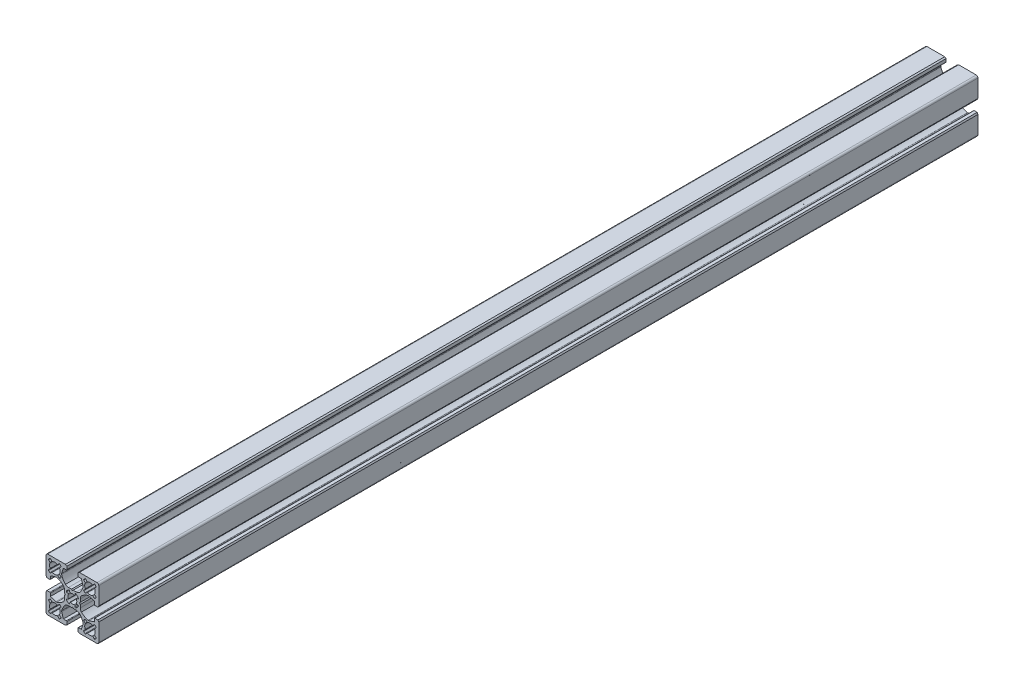
SolidWorks part; units mm, degrees
ref_plane "정면" through (0, 0, 0) normal (0, 0, 1) x (1, 0, 0)
ref_plane "윗면" through (0, 0, 0) normal (0, 1, 0) x (1, 0, 0)
ref_plane "우측면" through (0, 0, 0) normal (1, 0, 0) x (0, 0, -1)
sketch "Model" plane through (0, 0, 0) normal (0, 0, 1) x (1, 0, 0)
  line L0 (465.6218, 205.5838) -> (465.6218, 209.9838) construction
  line L1 (463.4218, 207.7838) -> (467.8218, 207.7838) construction
  line L2 (462.8793, 206.102) -> (462.1388, 205.3614)
  line L3 (463.1994, 204.3007) -> (463.94, 205.0413)
  line L4 (467.3037, 205.0413) -> (468.0443, 204.3007)
  line L5 (469.1049, 205.3614) -> (468.3643, 206.102)
  line L6 (468.3643, 209.4657) -> (469.1049, 210.2063)
  line L7 (468.0443, 211.2669) -> (467.3037, 210.5263)
  line L8 (463.94, 210.5263) -> (463.1994, 211.2669)
  line L9 (462.1388, 210.2063) -> (462.8793, 209.4657)
  line L10 (463.4211, 187.7832) -> (467.8211, 187.7829) construction
  line L11 (465.6212, 189.9831) -> (465.6209, 185.5831) construction
  line L12 (462.8787, 189.4651) -> (462.1382, 190.2057)
  line L13 (463.1989, 191.2663) -> (463.9394, 190.5257)
  line L14 (467.3031, 190.5254) -> (468.0438, 191.2659)
  line L15 (469.1043, 190.2052) -> (468.3637, 189.4647)
  line L16 (468.3634, 186.101) -> (469.1039, 185.3604)
  line L17 (468.0432, 184.2998) -> (467.3027, 185.0404)
  line L18 (463.939, 185.0407) -> (463.1984, 184.3002)
  line L19 (462.1378, 185.3609) -> (462.8784, 186.1014)
  line L20 (448.3673, 189.4651) -> (449.1078, 190.2057)
  line L21 (448.0471, 191.2663) -> (447.3066, 190.5257)
  line L22 (443.9429, 190.5254) -> (443.2023, 191.2659)
  line L23 (442.1417, 190.2052) -> (442.8823, 189.4647)
  line L24 (442.8826, 186.101) -> (442.1421, 185.3604)
  line L25 (443.2028, 184.2998) -> (443.9433, 185.0404)
  line L26 (447.307, 185.0407) -> (448.0476, 184.3002)
  line L27 (449.1082, 185.3609) -> (448.3676, 186.1014)
  line L28 (445.6248, 189.9831) -> (445.6251, 185.5831) construction
  line L29 (447.825, 187.7832) -> (443.425, 187.7829) construction
  line L30 (447.8242, 207.7838) -> (443.4242, 207.7838) construction
  line L31 (445.6242, 205.5838) -> (445.6242, 209.9838) construction
  line L32 (471.0819, 197.7838) -> (439.4, 197.7838) construction
  line L33 (455.6242, 181.8427) -> (455.6242, 213.7801) construction
  line L34 (457.2103, 201.0212) -> (457.0767, 200.2802)
  line L35 (454.1716, 200.2802) -> (454.0381, 201.0212)
  line L36 (452.3868, 199.37) -> (453.1278, 199.2364)
  line L37 (453.1278, 196.3313) -> (452.3868, 196.1977)
  line L38 (454.0381, 194.5465) -> (454.1716, 195.2874)
  line L39 (457.0767, 195.2874) -> (457.2103, 194.5465)
  line L40 (458.8615, 196.1977) -> (458.1206, 196.3313)
  line L41 (458.1206, 199.2364) -> (458.8615, 199.37)
  line L42 (448.3667, 206.102) -> (449.1073, 205.3614)
  line L43 (448.0466, 204.3007) -> (447.306, 205.0413)
  line L44 (443.9423, 205.0413) -> (443.2018, 204.3007)
  line L45 (442.1411, 205.3614) -> (442.8817, 206.102)
  line L46 (442.8817, 209.4657) -> (442.1411, 210.2063)
  line L47 (443.2018, 211.2669) -> (443.9423, 210.5263)
  line L48 (447.306, 210.5263) -> (448.0466, 211.2669)
  line L49 (449.1073, 210.2063) -> (448.3667, 209.4657)
  line L50 (459.5742, 182.7838) -> (458.7742, 183.2838)
  line L51 (458.7742, 183.2838) -> (458.7742, 184.9838)
  line L52 (459.0742, 185.2838) -> (460.7242, 185.2838)
  line L53 (460.7242, 185.2838) -> (461.7118, 188.3356)
  line L54 (457.842, 193.2838) -> (456.1242, 193.2838)
  line L55 (456.1242, 193.2838) -> (455.6242, 193.7838)
  line L56 (455.6242, 193.7838) -> (455.1242, 193.2838)
  line L57 (455.1242, 193.2838) -> (453.4063, 193.2838)
  line L58 (449.5366, 188.3356) -> (450.5242, 185.2838)
  line L59 (450.5242, 185.2838) -> (452.1742, 185.2838)
  line L60 (452.4742, 184.9838) -> (452.4742, 183.2838)
  line L61 (452.4742, 183.2838) -> (451.6742, 182.7838)
  line L62 (451.6742, 182.7838) -> (441.6242, 182.7838)
  line L63 (440.6242, 183.7838) -> (440.6242, 193.8338)
  line L64 (440.6242, 193.8338) -> (441.1242, 194.6338)
  line L65 (441.1242, 194.6338) -> (442.8242, 194.6338)
  line L66 (443.1242, 194.3338) -> (443.1242, 192.6838)
  line L67 (443.1242, 192.6838) -> (446.1759, 191.6962)
  line L68 (451.1242, 195.566) -> (451.1242, 197.2838)
  line L69 (451.1242, 197.2838) -> (451.6242, 197.7838)
  line L70 (451.6242, 197.7838) -> (451.1242, 198.2838)
  line L71 (451.1242, 198.2838) -> (451.1242, 200.0017)
  line L72 (446.1759, 203.8714) -> (443.1242, 202.8838)
  line L73 (443.1242, 202.8838) -> (443.1242, 201.2338)
  line L74 (442.8242, 200.9338) -> (441.1242, 200.9338)
  line L75 (441.1242, 200.9338) -> (440.6242, 201.7338)
  line L76 (440.6242, 201.7338) -> (440.6242, 211.7838)
  line L77 (441.6242, 212.7838) -> (451.6742, 212.7838)
  line L78 (451.6742, 212.7838) -> (452.4742, 212.2838)
  line L79 (452.4742, 212.2838) -> (452.4742, 210.5838)
  line L80 (452.1742, 210.2838) -> (450.5242, 210.2838)
  line L81 (450.5242, 210.2838) -> (449.5366, 207.2321)
  line L82 (453.4063, 202.2838) -> (455.1242, 202.2838)
  line L83 (455.1242, 202.2838) -> (455.6242, 201.7838)
  line L84 (455.6242, 201.7838) -> (456.1242, 202.2838)
  line L85 (456.1242, 202.2838) -> (457.842, 202.2838)
  line L86 (461.7118, 207.2321) -> (460.7242, 210.2838)
  line L87 (460.7242, 210.2838) -> (459.0742, 210.2838)
  line L88 (458.7742, 210.5838) -> (458.7742, 212.2838)
  line L89 (458.7742, 212.2838) -> (459.5742, 212.7838)
  line L90 (459.5742, 212.7838) -> (469.6242, 212.7838)
  line L91 (470.6242, 211.7838) -> (470.6242, 201.7338)
  line L92 (470.6242, 201.7338) -> (470.1242, 200.9338)
  line L93 (470.1242, 200.9338) -> (468.4242, 200.9338)
  line L94 (468.1242, 201.2338) -> (468.1242, 202.8838)
  line L95 (468.1242, 202.8838) -> (465.0724, 203.8714)
  line L96 (460.1242, 200.0017) -> (460.1242, 198.2838)
  line L97 (460.1242, 198.2838) -> (459.6242, 197.7838)
  line L98 (459.6242, 197.7838) -> (460.1242, 197.2838)
  line L99 (460.1242, 197.2838) -> (460.1242, 195.566)
  line L100 (465.0724, 191.6962) -> (468.1242, 192.6838)
  line L101 (468.1242, 192.6838) -> (468.1242, 194.3338)
  line L102 (468.4242, 194.6338) -> (470.1242, 194.6338)
  line L103 (470.1242, 194.6338) -> (470.6242, 193.8338)
  line L104 (470.6242, 193.8338) -> (470.6242, 183.7838)
  line L105 (469.6242, 182.7838) -> (459.5742, 182.7838)
  arc A0 (462.8793, 206.102) -> (462.9358, 206.4477) centre (462.6672, 206.3141) ccw
  arc A1 (462.1388, 205.3614) -> (462.1172, 204.9611) centre (462.3509, 205.1493) ccw
  arc A2 (462.1172, 204.9611) -> (462.7991, 204.2792) centre (465.6218, 207.7838) ccw
  arc A3 (462.7991, 204.2792) -> (463.1994, 204.3007) centre (462.9873, 204.5129) ccw
  arc A4 (464.2857, 205.0978) -> (463.94, 205.0413) centre (464.1521, 204.8292) ccw
  arc A5 (464.2857, 205.0978) -> (466.9579, 205.0978) centre (465.6218, 207.7838) ccw
  arc A6 (467.3037, 205.0413) -> (466.9579, 205.0978) centre (467.0916, 204.8292) ccw
  arc A7 (468.0443, 204.3007) -> (468.4446, 204.2792) centre (468.2564, 204.5129) ccw
  arc A8 (468.4446, 204.2792) -> (469.1264, 204.9611) centre (465.6218, 207.7838) ccw
  arc A9 (469.1264, 204.9611) -> (469.1049, 205.3614) centre (468.8928, 205.1493) ccw
  arc A10 (468.3079, 206.4477) -> (468.3643, 206.102) centre (468.5765, 206.3141) ccw
  arc A11 (468.3079, 206.4477) -> (468.3079, 209.1199) centre (465.6218, 207.7838) ccw
  arc A12 (468.3643, 209.4657) -> (468.3079, 209.1199) centre (468.5765, 209.2536) ccw
  arc A13 (469.1049, 210.2063) -> (469.1264, 210.6066) centre (468.8928, 210.4184) ccw
  arc A14 (469.1264, 210.6066) -> (468.4446, 211.2884) centre (465.6218, 207.7838) ccw
  arc A15 (468.4446, 211.2884) -> (468.0443, 211.2669) centre (468.2564, 211.0548) ccw
  arc A16 (466.9579, 210.4699) -> (467.3037, 210.5263) centre (467.0916, 210.7385) ccw
  arc A17 (466.9579, 210.4699) -> (464.2857, 210.4699) centre (465.6218, 207.7838) ccw
  arc A18 (463.94, 210.5263) -> (464.2857, 210.4699) centre (464.1521, 210.7385) ccw
  arc A19 (463.1994, 211.2669) -> (462.7991, 211.2884) centre (462.9873, 211.0548) ccw
  arc A20 (462.7991, 211.2884) -> (462.1172, 210.6066) centre (465.6218, 207.7838) ccw
  arc A21 (462.1172, 210.6066) -> (462.1388, 210.2063) centre (462.3509, 210.4184) ccw
  arc A22 (462.9358, 209.1199) -> (462.8793, 209.4657) centre (462.6672, 209.2536) ccw
  arc A23 (462.9358, 209.1199) -> (462.9358, 206.4477) centre (465.6218, 207.7838) ccw
  arc A24 (462.9351, 189.1194) -> (462.8787, 189.4651) centre (462.6665, 189.253) ccw
  arc A25 (462.1167, 190.6061) -> (462.1382, 190.2057) centre (462.3503, 190.4179) ccw
  arc A26 (462.7986, 191.2879) -> (462.1167, 190.6061) centre (465.6211, 187.7831) ccw
  arc A27 (463.1989, 191.2663) -> (462.7986, 191.2879) centre (462.9868, 191.0542) ccw
  arc A28 (463.9394, 190.5257) -> (464.2852, 190.4692) centre (464.1516, 190.7378) ccw
  arc A29 (466.9574, 190.469) -> (464.2852, 190.4692) centre (465.6211, 187.7831) ccw
  arc A30 (466.9574, 190.469) -> (467.3031, 190.5254) centre (467.091, 190.7376) ccw
  arc A31 (468.4441, 191.2874) -> (468.0438, 191.2659) centre (468.2559, 191.0538) ccw
  arc A32 (469.1259, 190.6055) -> (468.4441, 191.2874) centre (465.6211, 187.7831) ccw
  arc A33 (469.1043, 190.2052) -> (469.1259, 190.6055) centre (468.8922, 190.4174) ccw
  arc A34 (468.3637, 189.4647) -> (468.3072, 189.119) centre (468.5758, 189.2525) ccw
  arc A35 (468.307, 186.4467) -> (468.3072, 189.119) centre (465.6211, 187.7831) ccw
  arc A36 (468.307, 186.4467) -> (468.3634, 186.101) centre (468.5756, 186.3131) ccw
  arc A37 (469.1254, 184.96) -> (469.1039, 185.3604) centre (468.8918, 185.1482) ccw
  arc A38 (468.4435, 184.2782) -> (469.1254, 184.96) centre (465.6211, 187.7831) ccw
  arc A39 (468.0432, 184.2998) -> (468.4435, 184.2782) centre (468.2554, 184.5119) ccw
  arc A40 (467.3027, 185.0404) -> (466.957, 185.0969) centre (467.0905, 184.8283) ccw
  arc A41 (464.2847, 185.0971) -> (466.957, 185.0969) centre (465.6211, 187.7831) ccw
  arc A42 (464.2847, 185.0971) -> (463.939, 185.0407) centre (464.1511, 184.8285) ccw
  arc A43 (462.798, 184.2787) -> (463.1984, 184.3002) centre (462.9862, 184.5123) ccw
  arc A44 (462.1162, 184.9606) -> (462.798, 184.2787) centre (465.6211, 187.7831) ccw
  arc A45 (462.1378, 185.3609) -> (462.1162, 184.9606) centre (462.3499, 185.1488) ccw
  arc A46 (462.8784, 186.1014) -> (462.9349, 186.4472) centre (462.6663, 186.3136) ccw
  arc A47 (462.9351, 189.1194) -> (462.9349, 186.4472) centre (465.6211, 187.7831) ccw
  arc A48 (448.3673, 189.4651) -> (448.3109, 189.1194) centre (448.5795, 189.253) ccw
  arc A49 (449.1078, 190.2057) -> (449.1293, 190.6061) centre (448.8957, 190.4179) ccw
  arc A50 (449.1293, 190.6061) -> (448.4474, 191.2879) centre (445.625, 187.7831) ccw
  arc A51 (448.4474, 191.2879) -> (448.0471, 191.2663) centre (448.2593, 191.0542) ccw
  arc A52 (446.9609, 190.4692) -> (447.3066, 190.5257) centre (447.0944, 190.7378) ccw
  arc A53 (446.9609, 190.4692) -> (444.2886, 190.469) centre (445.625, 187.7831) ccw
  arc A54 (443.9429, 190.5254) -> (444.2886, 190.469) centre (444.155, 190.7376) ccw
  arc A55 (443.2023, 191.2659) -> (442.8019, 191.2874) centre (442.9901, 191.0538) ccw
  arc A56 (442.8019, 191.2874) -> (442.1201, 190.6055) centre (445.625, 187.7831) ccw
  arc A57 (442.1201, 190.6055) -> (442.1417, 190.2052) centre (442.3538, 190.4174) ccw
  arc A58 (442.9388, 189.119) -> (442.8823, 189.4647) centre (442.6702, 189.2525) ccw
  arc A59 (442.9388, 189.119) -> (442.939, 186.4467) centre (445.625, 187.7831) ccw
  arc A60 (442.8826, 186.101) -> (442.939, 186.4467) centre (442.6704, 186.3131) ccw
  arc A61 (442.1421, 185.3604) -> (442.1206, 184.96) centre (442.3542, 185.1482) ccw
  arc A62 (442.1206, 184.96) -> (442.8025, 184.2782) centre (445.625, 187.7831) ccw
  arc A63 (442.8025, 184.2782) -> (443.2028, 184.2998) centre (442.9907, 184.5119) ccw
  arc A64 (444.2891, 185.0969) -> (443.9433, 185.0404) centre (444.1555, 184.8283) ccw
  arc A65 (444.2891, 185.0969) -> (446.9613, 185.0971) centre (445.625, 187.7831) ccw
  arc A66 (447.307, 185.0407) -> (446.9613, 185.0971) centre (447.0949, 184.8285) ccw
  arc A67 (448.0476, 184.3002) -> (448.448, 184.2787) centre (448.2598, 184.5123) ccw
  arc A68 (448.448, 184.2787) -> (449.1298, 184.9606) centre (445.625, 187.7831) ccw
  arc A69 (449.1298, 184.9606) -> (449.1082, 185.3609) centre (448.8961, 185.1488) ccw
  arc A70 (448.3111, 186.4472) -> (448.3676, 186.1014) centre (448.5797, 186.3136) ccw
  arc A71 (448.3111, 186.4472) -> (448.3109, 189.1194) centre (445.625, 187.7831) ccw
  arc A72 (458.8615, 199.37) -> (459.0666, 199.8178) centre (458.8083, 199.6652) ccw
  arc A73 (459.0666, 199.8178) -> (457.6582, 201.2262) centre (455.623, 197.7827) ccw
  arc A74 (457.6582, 201.2262) -> (457.2103, 201.0212) centre (457.5055, 200.9679) ccw
  arc A75 (456.6575, 200.0603) -> (457.0767, 200.2802) centre (456.7815, 200.3335) ccw
  arc A76 (456.6575, 200.0603) -> (454.5909, 200.0603) centre (455.6242, 197.7838) ccw
  arc A77 (454.1716, 200.2802) -> (454.5909, 200.0603) centre (454.4669, 200.3335) ccw
  arc A78 (454.0381, 201.0212) -> (453.5902, 201.2262) centre (453.7428, 200.9679) ccw
  arc A79 (453.5902, 201.2262) -> (452.1818, 199.8178) centre (455.6253, 197.7827) ccw
  arc A80 (452.1818, 199.8178) -> (452.3868, 199.37) centre (452.4401, 199.6652) ccw
  arc A81 (453.3477, 198.8171) -> (453.1278, 199.2364) centre (453.0745, 198.9411) ccw
  arc A82 (453.3477, 198.8171) -> (453.3477, 196.7505) centre (455.6242, 197.7838) ccw
  arc A83 (453.1278, 196.3313) -> (453.3477, 196.7505) centre (453.0745, 196.6265) ccw
  arc A84 (452.3868, 196.1977) -> (452.1818, 195.7498) centre (452.4401, 195.9025) ccw
  arc A85 (452.1818, 195.7498) -> (453.5902, 194.3414) centre (455.6253, 197.785) ccw
  arc A86 (453.5902, 194.3414) -> (454.0381, 194.5465) centre (453.7428, 194.5997) ccw
  arc A87 (454.5909, 195.5074) -> (454.1716, 195.2874) centre (454.4669, 195.2342) ccw
  arc A88 (454.5909, 195.5074) -> (456.6575, 195.5074) centre (455.6242, 197.7838) ccw
  arc A89 (457.0767, 195.2874) -> (456.6575, 195.5074) centre (456.7815, 195.2342) ccw
  arc A90 (457.2103, 194.5465) -> (457.6582, 194.3414) centre (457.5055, 194.5997) ccw
  arc A91 (457.6582, 194.3414) -> (459.0666, 195.7498) centre (455.623, 197.785) ccw
  arc A92 (459.0666, 195.7498) -> (458.8615, 196.1977) centre (458.8083, 195.9025) ccw
  arc A93 (457.9006, 196.7505) -> (458.1206, 196.3313) centre (458.1738, 196.6265) ccw
  arc A94 (457.9006, 196.7505) -> (457.9006, 198.8171) centre (455.6242, 197.7838) ccw
  arc A95 (458.1206, 199.2364) -> (457.9006, 198.8171) centre (458.1738, 198.9411) ccw
  arc A96 (448.3102, 206.4477) -> (448.3667, 206.102) centre (448.5788, 206.3141) ccw
  arc A97 (449.1288, 204.9611) -> (449.1073, 205.3614) centre (448.8951, 205.1493) ccw
  arc A98 (448.4469, 204.2792) -> (449.1288, 204.9611) centre (445.6242, 207.7838) ccw
  arc A99 (448.0466, 204.3007) -> (448.4469, 204.2792) centre (448.2587, 204.5129) ccw
  arc A100 (447.306, 205.0413) -> (446.9603, 205.0978) centre (447.0939, 204.8292) ccw
  arc A101 (444.2881, 205.0978) -> (446.9603, 205.0978) centre (445.6242, 207.7838) ccw
  arc A102 (444.2881, 205.0978) -> (443.9423, 205.0413) centre (444.1545, 204.8292) ccw
  arc A103 (442.8014, 204.2792) -> (443.2018, 204.3007) centre (442.9896, 204.5129) ccw
  arc A104 (442.1196, 204.9611) -> (442.8014, 204.2792) centre (445.6242, 207.7838) ccw
  arc A105 (442.1411, 205.3614) -> (442.1196, 204.9611) centre (442.3532, 205.1493) ccw
  arc A106 (442.8817, 206.102) -> (442.9381, 206.4477) centre (442.6695, 206.3141) ccw
  arc A107 (442.9381, 209.1199) -> (442.9381, 206.4477) centre (445.6242, 207.7838) ccw
  arc A108 (442.9381, 209.1199) -> (442.8817, 209.4657) centre (442.6695, 209.2536) ccw
  arc A109 (442.1196, 210.6066) -> (442.1411, 210.2063) centre (442.3532, 210.4184) ccw
  arc A110 (442.8014, 211.2884) -> (442.1196, 210.6066) centre (445.6242, 207.7838) ccw
  arc A111 (443.2018, 211.2669) -> (442.8014, 211.2884) centre (442.9896, 211.0548) ccw
  arc A112 (443.9423, 210.5263) -> (444.2881, 210.4699) centre (444.1545, 210.7385) ccw
  arc A113 (446.9603, 210.4699) -> (444.2881, 210.4699) centre (445.6242, 207.7838) ccw
  arc A114 (446.9603, 210.4699) -> (447.306, 210.5263) centre (447.0939, 210.7385) ccw
  arc A115 (448.4469, 211.2884) -> (448.0466, 211.2669) centre (448.2587, 211.0548) ccw
  arc A116 (449.1288, 210.6066) -> (448.4469, 211.2884) centre (445.6242, 207.7838) ccw
  arc A117 (449.1073, 210.2063) -> (449.1288, 210.6066) centre (448.8951, 210.4184) ccw
  arc A118 (448.3667, 209.4657) -> (448.3102, 209.1199) centre (448.5788, 209.2536) ccw
  arc A119 (448.3102, 206.4477) -> (448.3102, 209.1199) centre (445.6242, 207.7838) ccw
  arc A120 (459.0742, 185.2838) -> (458.7742, 184.9838) centre (459.0742, 184.9838) ccw
  arc A121 (461.7118, 188.3356) -> (461.7375, 188.856) centre (460.7604, 188.6435) ccw
  arc A122 (461.7375, 188.856) -> (459.6282, 192.6941) centre (452.2648, 186.1487) ccw
  arc A123 (459.6282, 192.6941) -> (457.842, 193.2838) centre (457.842, 190.2838) ccw
  arc A124 (453.4063, 193.2838) -> (451.6202, 192.6941) centre (453.4063, 190.2838) ccw
  arc A125 (451.6202, 192.6941) -> (449.5108, 188.856) centre (458.9836, 186.1487) ccw
  arc A126 (449.5108, 188.856) -> (449.5366, 188.3356) centre (450.488, 188.6435) ccw
  arc A127 (452.4742, 184.9838) -> (452.1742, 185.2838) centre (452.1742, 184.9838) ccw
  arc A128 (440.6242, 183.7838) -> (441.6242, 182.7838) centre (441.6242, 183.7838) ccw
  arc A129 (443.1242, 194.3338) -> (442.8242, 194.6338) centre (442.8242, 194.3338) ccw
  arc A130 (446.1759, 191.6962) -> (446.6963, 191.6705) centre (446.4838, 192.6476) ccw
  arc A131 (446.6963, 191.6705) -> (450.5345, 193.7798) centre (443.9891, 201.1432) ccw
  arc A132 (450.5345, 193.7798) -> (451.1242, 195.566) centre (448.1242, 195.566) ccw
  arc A133 (451.1242, 200.0017) -> (450.5345, 201.7878) centre (448.1242, 200.0017) ccw
  arc A134 (450.5345, 201.7878) -> (446.6963, 203.8972) centre (443.9891, 194.4244) ccw
  arc A135 (446.6963, 203.8972) -> (446.1759, 203.8714) centre (446.4838, 202.92) ccw
  arc A136 (442.8242, 200.9338) -> (443.1242, 201.2338) centre (442.8242, 201.2338) ccw
  arc A137 (441.6242, 212.7838) -> (440.6242, 211.7838) centre (441.6242, 211.7838) ccw
  arc A138 (452.1742, 210.2838) -> (452.4742, 210.5838) centre (452.1742, 210.5838) ccw
  arc A139 (449.5366, 207.2321) -> (449.5108, 206.7117) centre (450.488, 206.9242) ccw
  arc A140 (449.5108, 206.7117) -> (451.6202, 202.8735) centre (458.9836, 209.4189) ccw
  arc A141 (451.6202, 202.8735) -> (453.4063, 202.2838) centre (453.4063, 205.2838) ccw
  arc A142 (457.842, 202.2838) -> (459.6282, 202.8735) centre (457.842, 205.2838) ccw
  arc A143 (459.6282, 202.8735) -> (461.7375, 206.7117) centre (452.2648, 209.4189) ccw
  arc A144 (461.7375, 206.7117) -> (461.7118, 207.2321) centre (460.7604, 206.9242) ccw
  arc A145 (458.7742, 210.5838) -> (459.0742, 210.2838) centre (459.0742, 210.5838) ccw
  arc A146 (470.6242, 211.7838) -> (469.6242, 212.7838) centre (469.6242, 211.7838) ccw
  arc A147 (468.1242, 201.2338) -> (468.4242, 200.9338) centre (468.4242, 201.2338) ccw
  arc A148 (465.0724, 203.8714) -> (464.552, 203.8972) centre (464.7645, 202.92) ccw
  arc A149 (464.552, 203.8972) -> (460.7139, 201.7878) centre (467.2593, 194.4244) ccw
  arc A150 (460.7139, 201.7878) -> (460.1242, 200.0017) centre (463.1242, 200.0017) ccw
  arc A151 (460.1242, 195.566) -> (460.7139, 193.7798) centre (463.1242, 195.566) ccw
  arc A152 (460.7139, 193.7798) -> (464.552, 191.6705) centre (467.2593, 201.1432) ccw
  arc A153 (464.552, 191.6705) -> (465.0724, 191.6962) centre (464.7645, 192.6476) ccw
  arc A154 (468.4242, 194.6338) -> (468.1242, 194.3338) centre (468.4242, 194.3338) ccw
  arc A155 (469.6242, 182.7838) -> (470.6242, 183.7838) centre (469.6242, 183.7838) ccw
  dimension "D1" = 30
  dimension "D2" = 30
  dimension "D3" = 15
  dimension "D4" = 15
extrude "보스-돌출1" add sketch "Model" along normal blind 500
